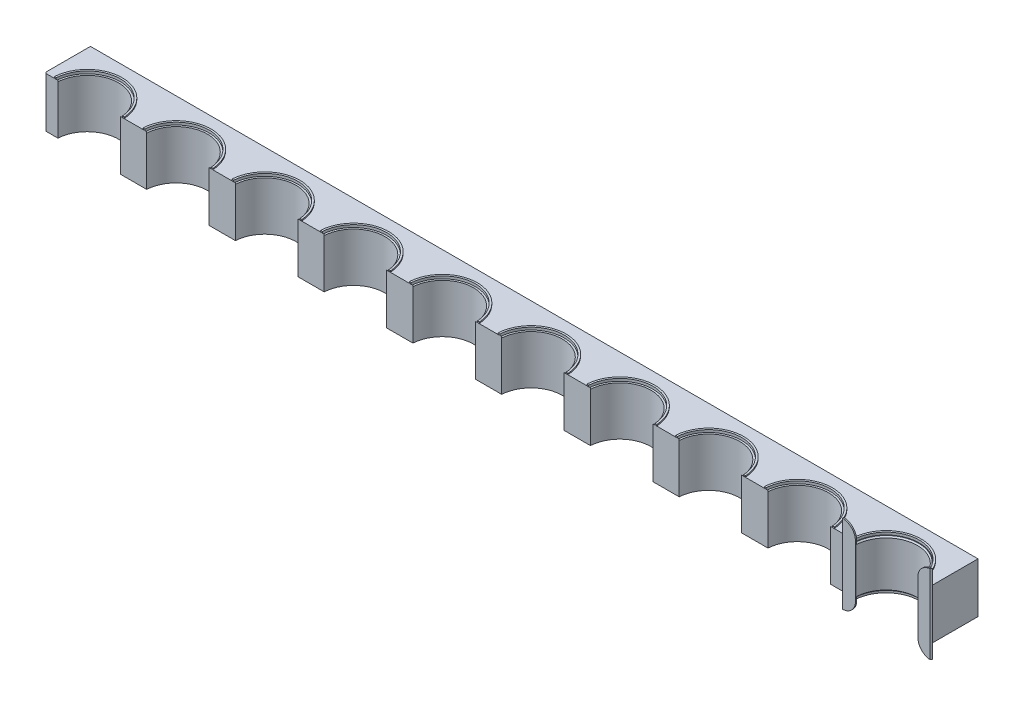
SolidWorks part; units mm, degrees
ref_plane "Front Plane" through (0, 0, 0) normal (0, 0, 1) x (1, 0, 0)
ref_plane "Top Plane" through (0, 0, 0) normal (0, 1, 0) x (1, 0, 0)
ref_plane "Right Plane" through (0, 0, 0) normal (1, 0, 0) x (0, 0, -1)
sketch "Sketch1" plane through (0, 0, 0) normal (0, 1, 0) x (1, 0, 0)
  line L0 (-63.391, 0) -> (0, 0) construction
  line L1 (0, 0) -> (63.391, 0) construction
  line L2 (0, 0) -> (0, -34.3713) construction
  line L3 (63.391, 0) -> (90.061, 0)
  line L4 (90.061, 0) -> (90.061, 95.25)
  line L5 (90.061, 95.25) -> (-90.061, 95.25)
  line L6 (-90.061, 95.25) -> (-90.061, 0)
  line L7 (-90.061, 0) -> (-63.391, 0)
  arc A0 (-63.391, 0) -> (63.391, 0) centre (0, -3.7192) cw
  dimension "D1" = 63.5
  dimension "D2" = 63.391
  dimension "D3" = 26.67
  dimension "D4" = 95.25
extrude "Boss-Extrude1" add sketch "Sketch1" along normal blind 101.6
sketch "Sketch2" plane through (0, 101.6, 0) normal (0, 1, 0) x (1, 0, 0)
  line L5 (67.1944, 0.2232) -> (63.391, 0)
  line L6 (-67.1944, 0.2232) -> (-63.391, 0)
  arc A3 (63.391, 0) -> (-63.391, 0) centre (0, -3.7192) ccw construction
  arc A4 (67.1944, 0.2232) -> (-67.1944, 0.2232) centre (0, -3.7192) ccw
  arc A5 (67.1944, 0.2232) -> (-67.1944, 0.2232) centre (0, -3.7192) ccw
  arc A6 (63.391, 0) -> (-63.391, 0) centre (0, -3.7192) ccw
  dimension "D1" = 3.81
extrude "Cut-Extrude1" cut sketch "Sketch2" against normal blind 2.54
sketch "Sketch3" plane through (0, 101.6, 0) normal (0, 1, 0) x (1, 0, 0)
  line L0 (-70.9979, 0.4463) -> (-67.1944, 0.2232)
  line L1 (67.1944, 0.2232) -> (70.9979, 0.4463)
  arc A2 (67.1944, 0.2232) -> (-67.1944, 0.2232) centre (0, -3.7192) ccw construction
  arc A3 (70.9979, 0.4463) -> (-70.9979, 0.4463) centre (0, -3.7192) ccw
  arc A4 (70.9979, 0.4463) -> (-70.9979, 0.4463) centre (0, -3.7192) ccw
  arc A5 (67.1944, 0.2232) -> (-67.1944, 0.2232) centre (0, -3.7192) ccw
  dimension "D1" = 3.81
extrude "Boss-Extrude2" add sketch "Sketch3" along normal blind 2.54
chamfer "Chamfer2" distance 2.54 angle 45 1 edges at (0, 99.06, -59.7808)
sketch "Sketch4" plane through (0, 0, 0) normal (0, 0, 1) x (1, 0, 0)
  line L0 (0, 0) -> (0, 101.6) construction
  line L1 (0, 50.8) -> (-90.061, 50.8) construction
  line L2 (-90.061, 101.6) -> (-90.061, 0) construction
  line L3 (-90.061, 50.8) -> (-63.391, 50.8)
  line L4 (-63.391, 96.52) -> (-63.391, 0) construction
  line L5 (-63.391, 50.8) -> (-63.391, 104.14)
  line L6 (-63.391, 104.14) -> (-90.061, 104.14)
  line L7 (-90.061, 104.14) -> (-90.061, 51.9342)
  line L8 (67.1944, 104.14) -> (-67.1944, 104.14) construction
  line L9 (-90.061, 104.14) -> (-90.061, 130.81)
  arc A0 (-63.391, 104.14) -> (-90.061, 130.81) centre (-90.061, 104.14) ccw
  point P7 (-90.061, 130.81)
  point P17 (-86.8767, 104.14)
  point P18 (-89.5632, 104.14)
  dimension "D1" = 52.2058
  dimension "D2" = 90
  dimension "D3" = 90
extrude "Boss-Extrude5" add sketch "Sketch4" along normal blind 2.54
ref_plane "Plane1" through (0, 50.8, 0) normal (0, 1, 0) x (1, 0, 0)
mirror "Mirror1" about plane through (0, 50.8, 0) normal (0, 1, 0) of "Boss-Extrude5", "Chamfer2", "Boss-Extrude2", "Cut-Extrude1"
ref_plane "Plane2" through (0, 0, 0) normal (1, 0, 0) x (0, 0, -1)
mirror "Mirror2" about plane through (0, 0, 0) normal (1, 0, 0) of "Boss-Extrude5"
mirror "Mirror3" about plane through (0, 50.8, 0) normal (0, 1, 0) of "Mirror2"
pattern_linear "LPattern14" count 10 spacing 180.086 along (-1, 0, 0) of "Boss-Extrude1", "Cut-Extrude1", "Boss-Extrude2"
chamfer "Chamfer3" distance 2.54 angle 45 1 edges at (-810.387, 101.6, -95.25)
chamfer "Chamfer4" distance 2.54 angle 45 7 edges at (90.061, 50.8, 2.54) (90.061, 130.81, 1.27) (90.061, -29.21, 1.27) (-1710.835, 50.8, 0) (90.061, 49.53, -95.25) (90.061, 100.33, -93.98) (-810.387, 0, -95.25)
